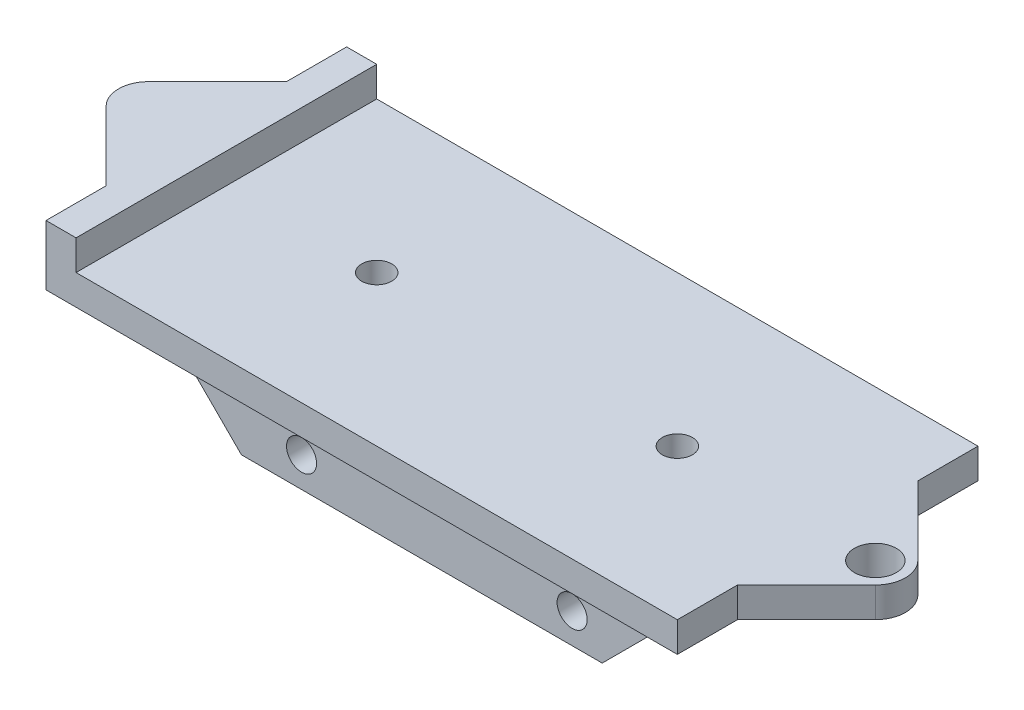
SolidWorks part; units mm, degrees
material "Cast Alloy Steel"
ref_plane "Front Plane" through (0, 0, 0) normal (0, 0, 1) x (1, 0, 0)
ref_plane "Top Plane" through (0, 0, 0) normal (0, 1, 0) x (1, 0, 0)
ref_plane "Right Plane" through (0, 0, 0) normal (1, 0, 0) x (0, 0, -1)
sketch "Sketch1" plane through (0, 0, 0) normal (0, 1, 0) x (1, 0, 0)
  line L0 (50, 15) -> (61.4645, 3.5355)
  line L1 (-55, -25) -> (50, -25)
  line L2 (-55, -25) -> (-55, 25)
  line L3 (-55, 25) -> (50, 25)
  line L4 (50, -25) -> (50, -15)
  line L5 (-55, -25) -> (50, 25) construction
  line L6 (-55, 25) -> (50, -25) construction
  line L7 (61.4645, -3.5355) -> (50, -15)
  line L9 (50, 15) -> (50, 25)
  arc A0 (61.4645, 3.5355) -> (61.4645, -3.5355) centre (57.9289, 0) cw
  circle A1 centre (57.9289, 0) radius 3.5
  dimension "D4" = 7
  dimension "D5" = 5
  dimension "D1" = 105
  dimension "D2" = 50
  dimension "D3" = 45
  dimension "D6" = 30
  dimension "D7" = 50
  dimension "D8" = 25
extrude "Boss-Extrude1" add sketch "Sketch1" along normal blind 5
sketch "Sketch2" plane through (0, 5, 0) normal (0, 1, 0) x (1, 0, 0)
  line L0 (-50, 25) -> (-50, -25)
  line L1 (50, 25) -> (-55, 25) construction
  line L2 (-55, -25) -> (50, -25) construction
  line L3 (-50, -25) -> (-55, -25)
  line L4 (-55, -25) -> (-55, -15)
  line L5 (-55, 25) -> (-55, -25) construction
  line L6 (-55, -15) -> (-66.4645, -3.5355)
  line L7 (-66.4645, 3.5355) -> (-55, 15)
  line L8 (-55, 15) -> (-55, 25)
  line L9 (-55, 25) -> (-50, 25)
  arc A0 (-66.4645, -3.5355) -> (-66.4645, 3.5355) centre (-62.9289, 0) cw
  dimension "D3" = 5
  dimension "D1" = 5
  dimension "D2" = 45
  dimension "D4" = 30
extrude "Boss-Extrude2" add sketch "Sketch2" along normal blind 5
sketch "Sketch3" plane through (0, 5, 0) normal (0, -1, 0) x (1, 0, 0)
  arc A0 (-66.4645, 3.5355) -> (-66.4645, -3.5355) centre (-62.9289, 0) ccw construction
  arc A1 (-66.4645, 3.5355) -> (-66.4645, -3.5355) centre (-62.9289, 0) ccw construction
  circle A2 centre (-62.9289, 0) radius 3.5
  dimension "D1" = 7
extrude "Boss-Extrude3" add sketch "Sketch3" along normal blind 5
sketch "Sketch4" plane through (0, 0, 0) normal (0, 0, 1) x (1, 0, 0)
  line L0 (-50, 0) -> (-32.5, -17.5)
  line L1 (-55, 0) -> (50, 0) construction
  line L2 (-32.5, -17.5) -> (27.5, -17.5)
  line L3 (27.5, -17.5) -> (45, 0)
  line L4 (-50, 0) -> (45, 0)
  line L5 (50, 5) -> (50, 0) construction
  line L6 (-55, 0) -> (50, 0) construction
  line L7 (-22.5, -12.5) -> (22.5, -12.5) construction
  circle A0 centre (-22.5, -12.5) radius 2.5
  circle A1 centre (22.5, -12.5) radius 2.5
  point P8 (0, -12.5)
  dimension "D4" = 5
  dimension "D5" = 5
  dimension "D1" = 45
  dimension "D2" = 5
  dimension "D3" = 5
  dimension "D6" = 45
  dimension "D7" = 17.5
  dimension "D8" = 5
extrude "Boss-Extrude4" add sketch "Sketch4" along normal mid plane 30
sketch "Sketch5" plane through (0, 0, 0) normal (0, -1, 0) x (1, 0, 0)
  line L0 (-50, 15) -> (-50, -15) construction
  line L1 (50, -10) -> (-50, -10)
  line L2 (50, -10) -> (50, 10)
  line L3 (50, 10) -> (-50, 10)
  line L4 (-50, -10) -> (-50, 10)
  line L5 (50, -10) -> (-50, 10) construction
  line L6 (50, 10) -> (-50, -10) construction
  point P0 (0, 0)
  dimension "D1" = 20
extrude "Cut-Extrude1" cut sketch "Sketch5" along normal up to next
sketch "Sketch6" plane through (0, 5, 0) normal (0, 1, 0) x (1, 0, 0)
  line L0 (50, 15) -> (50, 25) construction
  line L1 (-25, 0) -> (25, 0) construction
  circle A0 centre (25, 0) radius 2.5
  circle A1 centre (-25, 0) radius 2.5
  dimension "D1" = 5
  dimension "D2" = 25
extrude "Cut-Extrude2" cut sketch "Sketch6" against normal up to next
chamfer "Chamfer1" distance 1 angle 45 1 edges at (-62.9289, 0, -3.5)
